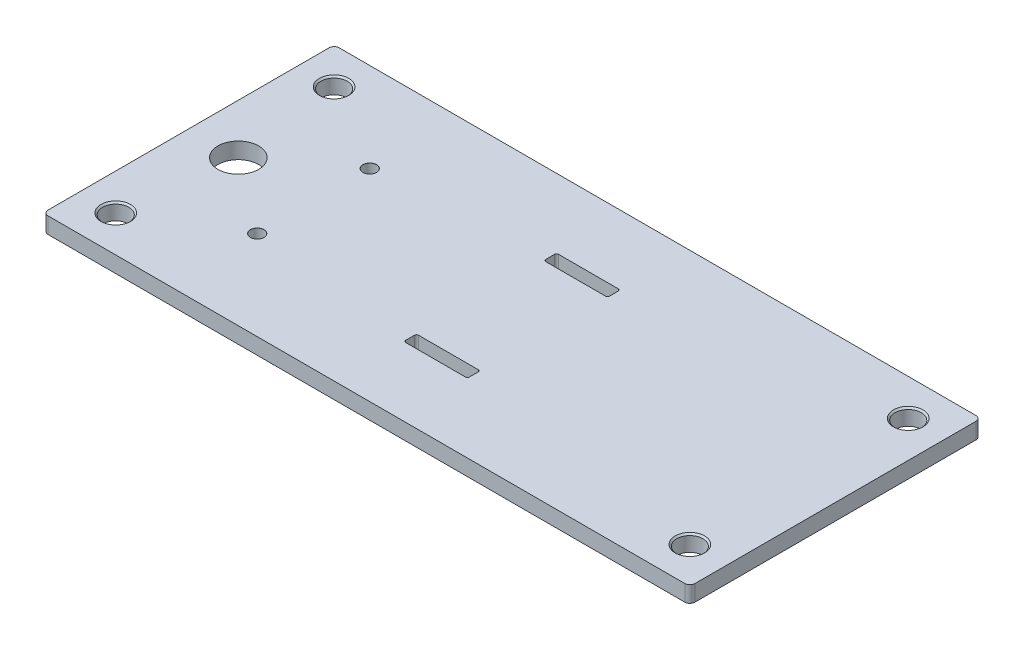
SolidWorks part; units mm, degrees
material "ABS"
ref_plane "Front Plane" through (0, 0, 0) normal (0, 0, 1) x (1, 0, 0)
ref_plane "Top Plane" through (0, 0, 0) normal (0, 1, 0) x (1, 0, 0)
ref_plane "Right Plane" through (0, 0, 0) normal (1, 0, 0) x (0, 0, -1)
sketch "Sketch1" plane through (0, 0, 0) normal (0, 1, 0) x (1, 0, 0)
  line L1 (-127, -57.15) -> (127, -57.15)
  line L2 (-127, -57.15) -> (-127, 57.15)
  line L3 (-127, 57.15) -> (127, 57.15)
  line L4 (127, -57.15) -> (127, 57.15)
  line L5 (-127, -57.15) -> (127, 57.15) construction
  line L6 (-127, 57.15) -> (127, -57.15) construction
  point P0 (0, 0)
  dimension "D1" = 254
  dimension "D2" = 114.3
extrude "Boss-Extrude1" add sketch "Sketch1" along normal blind 6.35
fillet "Fillet1" radius 2 4 edges at (-127, 3.175, -57.15) (127, 3.175, -57.15) (-127, 3.175, 57.15) (127, 3.175, 57.15)
sketch "Sketch6" plane through (0, 6.35, 0) normal (0, 1, 0) x (1, 0, 0)
  line L0 (127, 0) -> (-127, 0) construction
  line L1 (127, -55.15) -> (127, 55.15) construction
  line L2 (-127, 55.15) -> (-127, -55.15) construction
  line L3 (0, 57.15) -> (0, -57.15) construction
  line L4 (125, 57.15) -> (-125, 57.15) construction
  line L5 (-125, -57.15) -> (125, -57.15) construction
  line L6 (-12.5, 25) -> (-12.5, 30)
  line L7 (-12.5, -25) -> (12.5, -25)
  line L8 (-12.5, -25) -> (-12.5, -30)
  line L9 (-12.5, -30) -> (12.5, -30)
  line L10 (12.5, -25) -> (12.5, -30)
  line L11 (-12.5, -25) -> (12.5, -30) construction
  line L12 (-12.5, -30) -> (12.5, -25) construction
  line L13 (-12.5, 30) -> (12.5, 30)
  line L14 (12.5, 25) -> (12.5, 30)
  line L15 (-12.5, 25) -> (12.5, 25)
  point P12 (0, -27.5)
  dimension "D1" = 25
  dimension "D2" = 5
  dimension "D3" = 25
extrude "Cut-Extrude1" cut sketch "Sketch6" against normal through all
fillet "Fillet2" radius 0.75 8 edges at (-12.5, 3.175, -25) (-12.5, 3.175, -30) (12.5, 3.175, -25) (12.5, 3.175, -30) (12.5, 3.175, 25) (12.5, 3.175, 30) (-12.5, 3.175, 30) (-12.5, 3.175, 25)
sketch "Sketch8" plane through (0, 6.35, 0) normal (0, 1, 0) x (1, 0, 0)
  point P0 (112.7125, 42.8625)
  point P1 (112.7125, -42.8675)
  point P3 (-112.7175, 42.8625)
  point P5 (-112.7175, -42.8675)
hole_wizard "3/8 Clearance Hole1" positions "Sketch8" profile "Sketch9" hole size "3/8" standard "ANSI Inch" end condition through all
sketch "Sketch9" plane through (112.7125, 6.35, -42.8625) normal (1, 0, 0) x (0, 0, 1)
  line L0 (0, 0) -> (0, 6.35)
  line L1 (0, 6.35) -> (5.1587, 6.35)
  line L2 (5.1587, 6.35) -> (5.1587, 0.635)
  line L3 (5.1587, 0.635) -> (5.7937, 0)
  line L5 (5.7937, 0) -> (0, 0)
  line L6 (-5.1587, 0.635) -> (-5.7937, 0) construction
  line L11 (0, -6.35) -> (0, 107.95) construction
  dimension "Thru Hole Dia." = 10.3175
  dimension "Thru Hole Depth" = 6.35
  dimension "Near C'Sink Dia." = 11.5875
  dimension "Near C'Sink Angle" = 90
sketch "Sketch10" plane through (0, 6.35, 0) normal (0, 1, 0) x (1, 0, 0)
  line L0 (0, 0) -> (-127, 0) construction
  line L1 (-127, 55.15) -> (-127, -55.15) construction
  circle A0 centre (-107.475, 0) radius 8
  dimension "D1" = 16
  dimension "D2" = 19.525
extrude "Cut-Extrude2" cut sketch "Sketch10" against normal through all
sketch "Sketch11" plane through (0, 6.35, 0) normal (0, 1, 0) x (1, 0, 0)
  line L0 (-127, 55.15) -> (-127, -55.15) construction
  line L1 (-88.9, 27.15) -> (-67, 27.15) construction
  line L2 (-88.9, 27.15) -> (-88.9, -27.15) construction
  line L3 (-88.9, -27.15) -> (-67, -27.15) construction
  line L4 (-67, 27.15) -> (-67, -27.15) construction
  point P5 (-77.95, -22.1)
  point P6 (-77.95, 22.1)
  point P25 (-88.9, 0)
  dimension "D1" = 54.3
  dimension "D2" = 21.9
  dimension "D3" = 10.95
  dimension "D4" = 5.05
  dimension "D5" = 44.2
  dimension "D6" = 38.1
  dimension "D7" = 10.95
hole_wizard "M3 Clearance Hole1" positions "Sketch11" profile "Sketch12" hole size "M3" standard "ANSI Metric" end condition through all
sketch "Sketch12" plane through (-77.95, 6.35, -22.1) normal (1, 0, 0) x (0, 0, 1)
  line L0 (0, 0) -> (0, 6.35)
  line L1 (0, 6.35) -> (2.65, 6.35)
  line L2 (2.65, 6.35) -> (2.65, 0.025)
  line L3 (2.65, 0.025) -> (2.675, 0)
  line L5 (2.675, 0) -> (0, 0)
  line L6 (-2.65, 0.025) -> (-2.675, 0) construction
  line L11 (0, -6.35) -> (0, 107.95) construction
  dimension "Thru Hole Dia." = 5.3
  dimension "Thru Hole Depth" = 6.35
  dimension "Near C'Sink Dia." = 5.35
  dimension "Near C'Sink Angle" = 90
